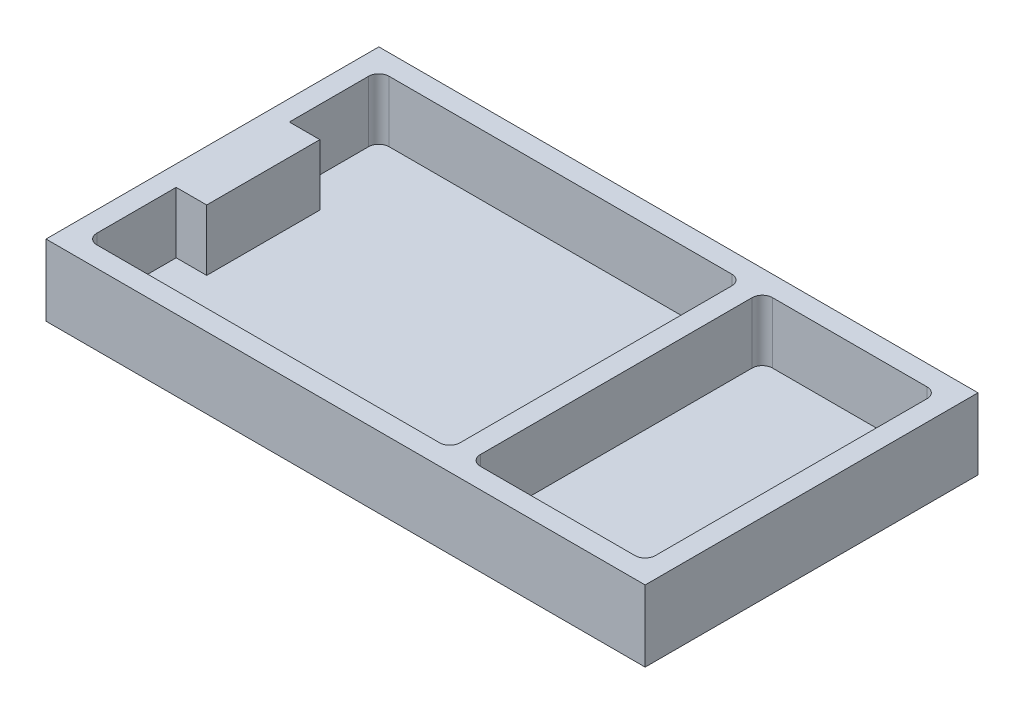
SolidWorks part; units mm, degrees
ref_plane "Front Plane" through (0, 0, 0) normal (0, 0, 1) x (1, 0, 0)
ref_plane "Top Plane" through (0, 0, 0) normal (0, 1, 0) x (1, 0, 0)
ref_plane "Right Plane" through (0, 0, 0) normal (1, 0, 0) x (0, 0, -1)
sketch "Sketch11" plane through (0, 0, 0) normal (0, 1, 0) x (1, 0, 0)
  line L0 (9.525, 6.35) -> (116.5413, 6.35)
  line L1 (0, 0) -> (187.0518, 0)
  line L2 (0, 0) -> (0, 103.9105)
  line L3 (0, 103.9105) -> (187.0518, 103.9105)
  line L4 (187.0518, 0) -> (187.0518, 103.9105)
  line L5 (180.7018, 9.525) -> (180.7018, 94.3855)
  line L6 (9.525, 97.5605) -> (116.5413, 97.5605)
  line L7 (6.35, 9.525) -> (6.35, 94.3855)
  line L8 (119.7163, 94.3855) -> (119.7163, 9.525)
  line L9 (126.0663, 94.3855) -> (126.0663, 9.525)
  line L10 (129.2413, 97.5605) -> (177.5268, 97.5605)
  line L11 (129.2413, 6.35) -> (177.5268, 6.35)
  line L12 (6.35, 97.5605) -> (180.7018, 97.5605) construction
  line L13 (119.7163, 97.5605) -> (119.7163, 6.35) construction
  line L14 (6.35, 6.35) -> (180.7018, 6.35) construction
  line L15 (126.0663, 97.5605) -> (126.0663, 6.35) construction
  line L16 (180.7018, 6.35) -> (180.7018, 97.5605) construction
  line L17 (6.35, 6.35) -> (6.35, 97.5605) construction
  arc A0 (119.7163, 94.3855) -> (116.5413, 97.5605) centre (116.5413, 94.3855) ccw
  arc A1 (129.2413, 97.5605) -> (126.0663, 94.3855) centre (129.2413, 94.3855) ccw
  arc A2 (180.7018, 94.3855) -> (177.5268, 97.5605) centre (177.5268, 94.3855) ccw
  arc A3 (180.7018, 9.525) -> (177.5268, 6.35) centre (177.5268, 9.525) cw
  arc A4 (126.0663, 9.525) -> (129.2413, 6.35) centre (129.2413, 9.525) ccw
  arc A5 (119.7163, 9.525) -> (116.5413, 6.35) centre (116.5413, 9.525) cw
  arc A6 (6.35, 94.3855) -> (9.525, 97.5605) centre (9.525, 94.3855) cw
  arc A7 (9.525, 6.35) -> (6.35, 9.525) centre (9.525, 9.525) cw
  dimension "D3" = 3.175
  dimension "D1" = 6.35
  dimension "D2" = 6.35
extrude "Extrude3" add sketch "Sketch11" along normal blind 19.05
sketch "Sketch12" plane through (0, 0, 0) normal (0, 1, 0) x (1, 0, 0)
  line L1 (0, 103.9105) -> (187.0518, 103.9105)
  line L2 (0, 103.9105) -> (0, 0)
  line L3 (0, 0) -> (187.0518, 0)
  line L4 (187.0518, 103.9105) -> (187.0518, 0)
extrude "Extrude4" add sketch "Sketch12" against normal blind 3.175
ref_plane "Plane2" through (6.35, 0, 0) normal (1, 0, 0) x (0, 0, -1)
sketch "Sketch15" plane through (6.35, 0, 0) normal (1, 0, 0) x (0, 0, -1)
  line L0 (51.9553, 19.05) -> (51.9553, 0) construction
  line L1 (94.3855, 19.05) -> (9.525, 19.05) construction
  line L2 (94.3855, 0) -> (9.525, 0) construction
  line L4 (34.2906, 19.05) -> (69.6199, 19.05)
  line L5 (34.2906, 19.05) -> (34.2906, 0)
  line L6 (34.2906, 0) -> (69.6199, 0)
  line L7 (69.6199, 19.05) -> (69.6199, 0)
  point P6 (51.9553, 9.525)
extrude "Extrude6" add sketch "Sketch15" along normal blind 9.525
ref_plane "Plane3" through (0, 0, 0) normal (-1, 0, 0) x (0, 0, 1)
sketch "Sketch16" plane through (0, 0, 0) normal (-1, 0, 0) x (0, 0, 1)
  line L0 (-51.9553, 19.05) -> (-51.9553, -3.175) construction
  line L1 (-103.9105, 19.05) -> (0, 19.05) construction
  line L2 (-103.9105, -3.175) -> (0, -3.175) construction
  circle A0 centre (-51.9553, 7.9375) radius 7.8105
